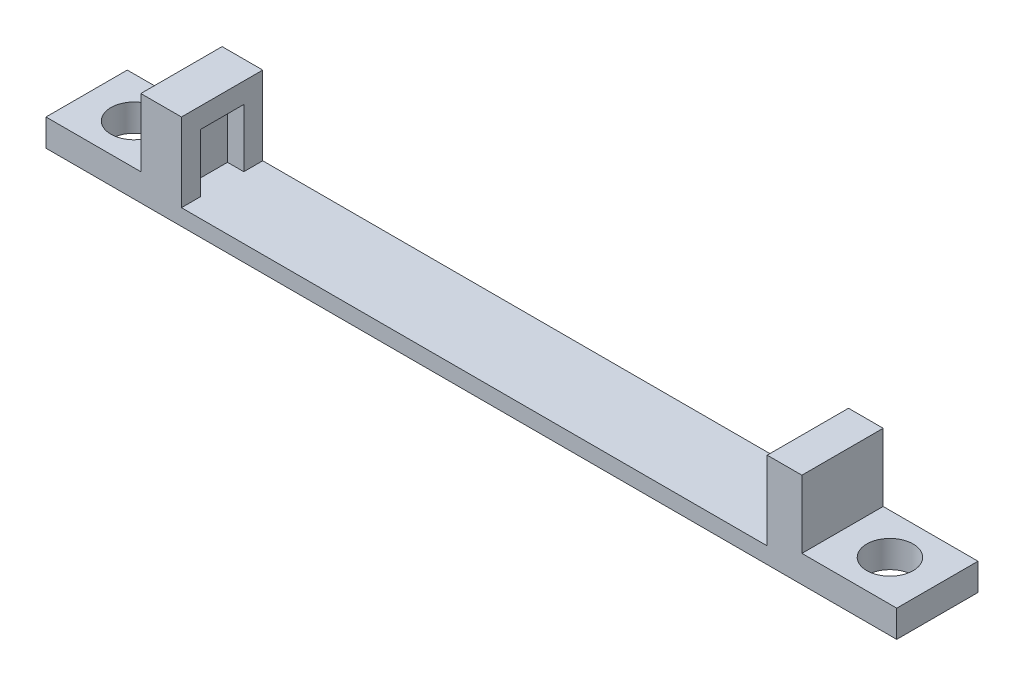
SolidWorks part; units mm, degrees
ref_plane "Front Plane" through (0, 0, 0) normal (0, 0, 1) x (1, 0, 0)
ref_plane "Top Plane" through (0, 0, 0) normal (0, 1, 0) x (1, 0, 0)
ref_plane "Right Plane" through (0, 0, 0) normal (1, 0, 0) x (0, 0, -1)
sketch "Sketch1" plane through (0, 0, 0) normal (0, 1, 0) x (1, 0, 0)
  line L1 (-13.9408, -5.8726) -> (65.8152, -5.8726)
  line L2 (-13.9408, -5.8726) -> (-13.9408, -13.4926)
  line L3 (-13.9408, -13.4926) -> (65.8152, -13.4926)
  line L4 (65.8152, -5.8726) -> (65.8152, -13.4926)
  dimension "D1" = 79.756
  dimension "D2" = 7.62
extrude "Boss-Extrude1" add sketch "Sketch1" along normal blind 8.89
sketch "Sketch2" plane through (0, 8.89, 0) normal (0, 1, 0) x (1, 0, 0)
  line L0 (-13.9408, -13.4926) -> (65.8152, -13.4926) construction
  line L1 (-13.9408, -5.8726) -> (-5.0508, -5.8726)
  line L2 (-13.9408, -5.8726) -> (-13.9408, -13.4926)
  line L3 (-13.9408, -13.4926) -> (-5.0508, -13.4926)
  line L4 (-5.0508, -5.8726) -> (-5.0508, -13.4926)
  dimension "D1" = 8.89
extrude "Cut-Extrude1" cut sketch "Sketch2" against normal blind 6.35
sketch "Sketch3" plane through (0, 8.89, 0) normal (0, 1, 0) x (1, 0, 0)
  line L0 (-5.0508, -13.4926) -> (65.8152, -13.4926) construction
  line L1 (65.8152, -5.8726) -> (56.9252, -5.8726)
  line L2 (65.8152, -5.8726) -> (65.8152, -13.4926)
  line L3 (65.8152, -13.4926) -> (56.9252, -13.4926)
  line L4 (56.9252, -5.8726) -> (56.9252, -13.4926)
  dimension "D1" = 8.89
extrude "Cut-Extrude2" cut sketch "Sketch3" against normal blind 6.35
sketch "Sketch4" plane through (0, 8.89, 0) normal (0, 1, 0) x (1, 0, 0)
  line L0 (56.9252, -5.8726) -> (-5.0508, -5.8726) construction
  line L1 (-1.2408, -5.8726) -> (53.674, -5.8726)
  line L2 (-1.2408, -5.8726) -> (-1.2408, -13.4926)
  line L3 (-1.2408, -13.4926) -> (53.674, -13.4926)
  line L4 (53.674, -5.8726) -> (53.674, -13.4926)
  line L5 (-5.0508, -13.4926) -> (56.9252, -13.4926) construction
  line L6 (-5.0508, -13.4926) -> (-5.0508, -5.8726) construction
  dimension "D1" = 54.9148
  dimension "D2" = 3.81
extrude "Cut-Extrude3" cut sketch "Sketch4" against normal blind 7.366
sketch "Sketch5" plane through (-1.2408, 0, 0) normal (1, 0, 0) x (0, 0, -1)
  line L0 (-13.4926, 1.524) -> (-13.4926, 8.89) construction
  line L1 (-11.7146, 6.985) -> (-7.6506, 6.985)
  line L2 (-11.7146, 6.985) -> (-11.7146, 1.524)
  line L3 (-11.7146, 1.524) -> (-7.6506, 1.524)
  line L4 (-7.6506, 6.985) -> (-7.6506, 1.524)
  line L5 (-5.8726, 1.524) -> (-13.4926, 1.524) construction
  dimension "D1" = 5.461
  dimension "D2" = 4.064
  dimension "D3" = 1.778
  dimension "D4" = 0
extrude "Cut-Extrude4" cut sketch "Sketch5" against normal blind 1.524
sketch "Sketch7" plane through (53.674, 0, 0) normal (-1, 0, 0) x (0, 0, 1)
  line L0 (5.8726, 1.524) -> (5.8726, 8.89) construction
  line L1 (7.8411, 6.985) -> (11.5241, 6.985)
  line L2 (7.8411, 6.985) -> (7.8411, 2.54)
  line L3 (7.8411, 2.54) -> (11.5241, 2.54)
  line L4 (11.5241, 6.985) -> (11.5241, 2.54)
  line L5 (13.4926, 1.524) -> (5.8726, 1.524) construction
  dimension "D1" = 4.445
  dimension "D2" = 3.683
  dimension "D3" = 1.9685
  dimension "D4" = 1.016
extrude "Boss-Extrude2" add sketch "Sketch7" along normal blind 1.524
sketch "Sketch8" plane through (0, 2.54, 0) normal (0, 1, 0) x (1, 0, 0)
  line L0 (-13.9408, -5.8726) -> (-13.9408, -13.4926) construction
  line L1 (-13.9408, -13.4926) -> (-5.0508, -13.4926) construction
  circle A0 centre (-9.4958, -9.6826) radius 2.1717
  dimension "D1" = 4.445
  dimension "D2" = 3.81
extrude "Cut-Extrude5" cut sketch "Sketch8" against normal blind 2.54
sketch "Sketch9" plane through (0, 2.54, 0) normal (0, 1, 0) x (1, 0, 0)
  line L1 (56.9252, -13.4926) -> (65.8152, -13.4926) construction
  line L2 (65.8152, -13.4926) -> (65.8152, -5.8726) construction
  circle A0 centre (61.3702, -9.6826) radius 2.1717
  dimension "D1" = 3.81
  dimension "D2" = 4.445
extrude "Cut-Extrude6" cut sketch "Sketch9" against normal blind 2.54
